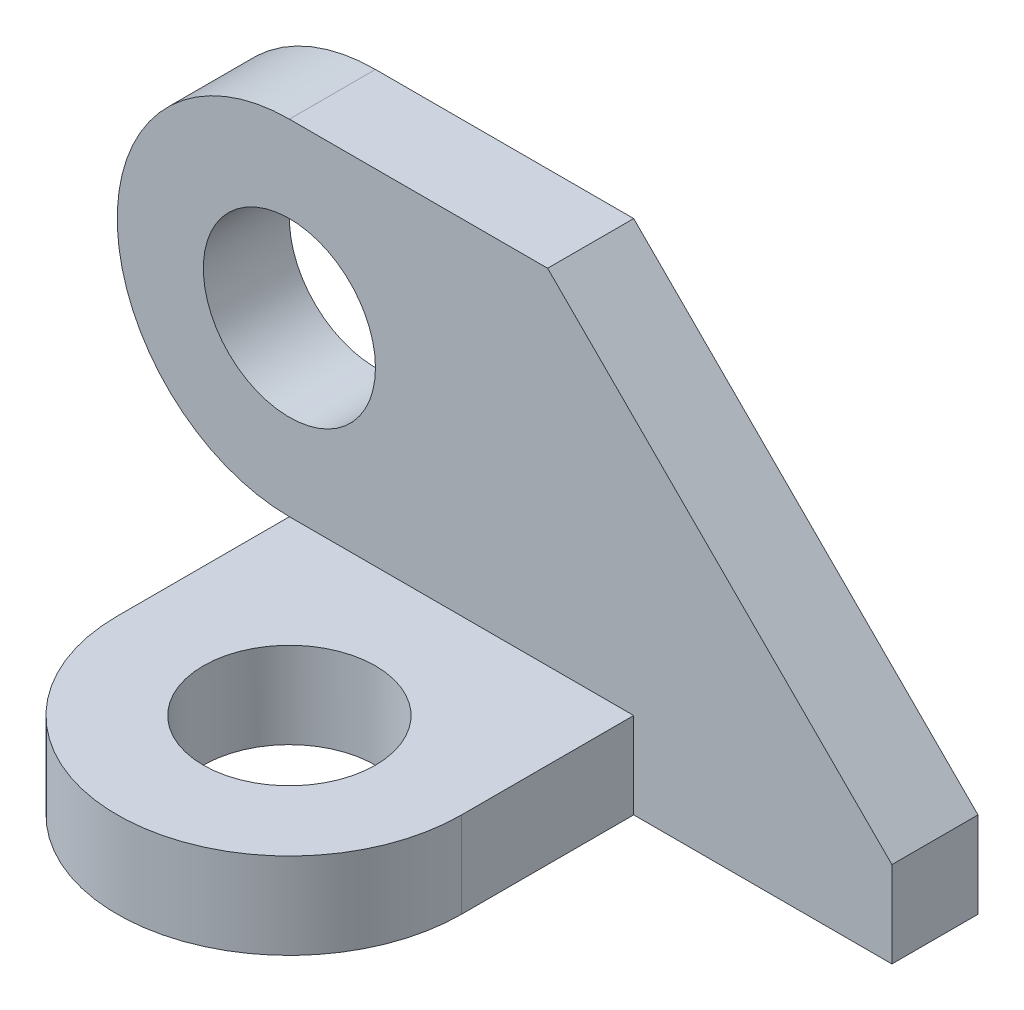
SolidWorks part; units mm, degrees
ref_plane "前基準面" through (0, 0, 0) normal (0, 0, 1) x (1, 0, 0)
ref_plane "上基準面" through (0, 0, 0) normal (0, 1, 0) x (1, 0, 0)
ref_plane "右基準面" through (0, 0, 0) normal (1, 0, 0) x (0, 0, -1)
sketch "草圖2" plane through (0, 0, 0) normal (0, 0, 1) x (1, 0, 0)
  line L0 (0, 10) -> (15, 10)
  line L1 (15, 10) -> (35, -10)
  line L2 (35, -10) -> (35, -15)
  line L3 (35, -15) -> (20, -15)
  line L4 (0, -10) -> (20, -10)
  line L5 (20, -10) -> (20, -15)
  circle A0 centre (0, 0) radius 5
  arc A1 (0, 10) -> (0, -10) centre (0, 0) ccw
  dimension "D1" = 10
  dimension "D2" = 10
  dimension "D3" = 15
  dimension "D4" = 20
  dimension "D5" = 5
  dimension "D6" = 20
  dimension "D7" = 45
  dimension "D8" = 5
extrude "填料-伸長3" add sketch "草圖2" along normal blind 5
sketch "草圖4" plane through (0, -10, 0) normal (0, -1, 0) x (1, 0, 0)
  line L1 (0, 0) -> (20, 0) construction
  line L2 (0, 0) -> (0, 15)
  line L4 (20, 0) -> (20, 15)
  line L5 (0, 0) -> (20, 0)
  arc A0 (0, 15) -> (20, 15) centre (10, 15) cw
  circle A1 centre (10, 15) radius 5
  dimension "D1" = 10
  dimension "D2" = 15
  dimension "D3" = 10
extrude "填料-伸長4" add sketch "草圖4" along normal up to surface (5 mm away) separate body up to face at (27.5, -15, 2.5)
sketch "草圖5" plane through (0, -15, 0) normal (0, -1, 0) x (1, 0, 0)
  line L1 (20, 5) -> (0, 5)
  line L2 (20, 5) -> (20, 0)
  line L3 (20, 0) -> (0, 0)
  line L4 (0, 5) -> (0, 0)
extrude "填料-伸長5" add sketch "草圖5" against normal blind 5
